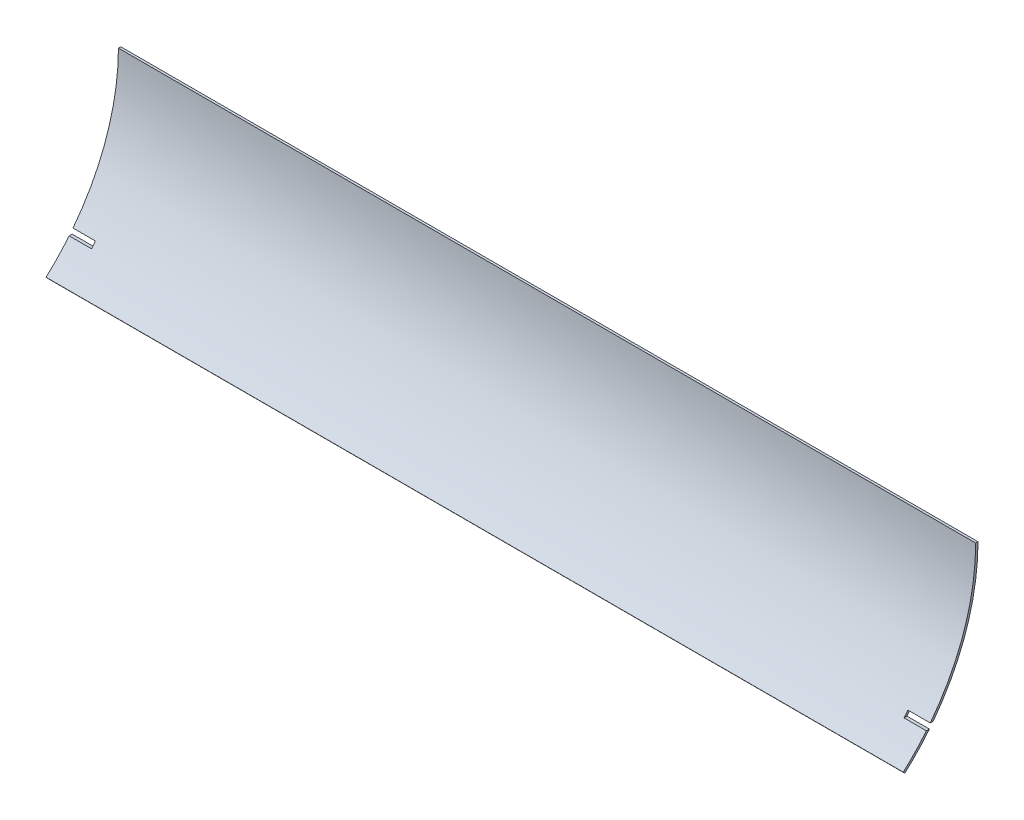
SolidWorks part; units mm, degrees
ref_plane "Front Plane" through (0, 0, 0) normal (0, 0, 1) x (1, 0, 0)
ref_plane "Top Plane" through (0, 0, 0) normal (0, 1, 0) x (1, 0, 0)
ref_plane "Right Plane" through (0, 0, 0) normal (1, 0, 0) x (0, 0, -1)
sketch "Sketch2" plane through (0, 0, 0) normal (1, 0, 0) x (0, 0, -1)
  arc A1 (99.5959, -111.125) -> (149.225, 0) centre (0, 0) ccw
  dimension "D1" = 149.225
extrude "Extrude-Thin1" add sketch "Sketch2" along normal blind 584.2 thin thin type mid plane wall 1.5875
sketch "Sketch3" plane through (0, 0, 0) normal (0, 0, 1) x (1, 0, 0)
  line L0 (0, -94.0239) -> (15.24, -94.0239)
  line L1 (0, 0) -> (0, -110.5339) construction
  line L2 (15.24, -94.0239) -> (15.24, -90.7219)
  line L3 (15.24, -90.7219) -> (0, -90.7219)
  line L4 (0, -90.7219) -> (0, -94.0239)
  line L5 (292.1, -110.5339) -> (292.1, 36.2793) construction
  line L6 (584.2, -110.5339) -> (0, -110.5339) construction
  line L7 (584.2, -90.7219) -> (584.2, -94.0239)
  line L8 (568.96, -90.7219) -> (584.2, -90.7219)
  line L9 (568.96, -94.0239) -> (568.96, -90.7219)
  line L10 (584.2, -94.0239) -> (568.96, -94.0239)
  dimension "D1" = 3.302
  dimension "D2" = 15.24
  dimension "D3" = 16.51
extrude "Cut-Extrude1" cut sketch "Sketch3" against normal through all
